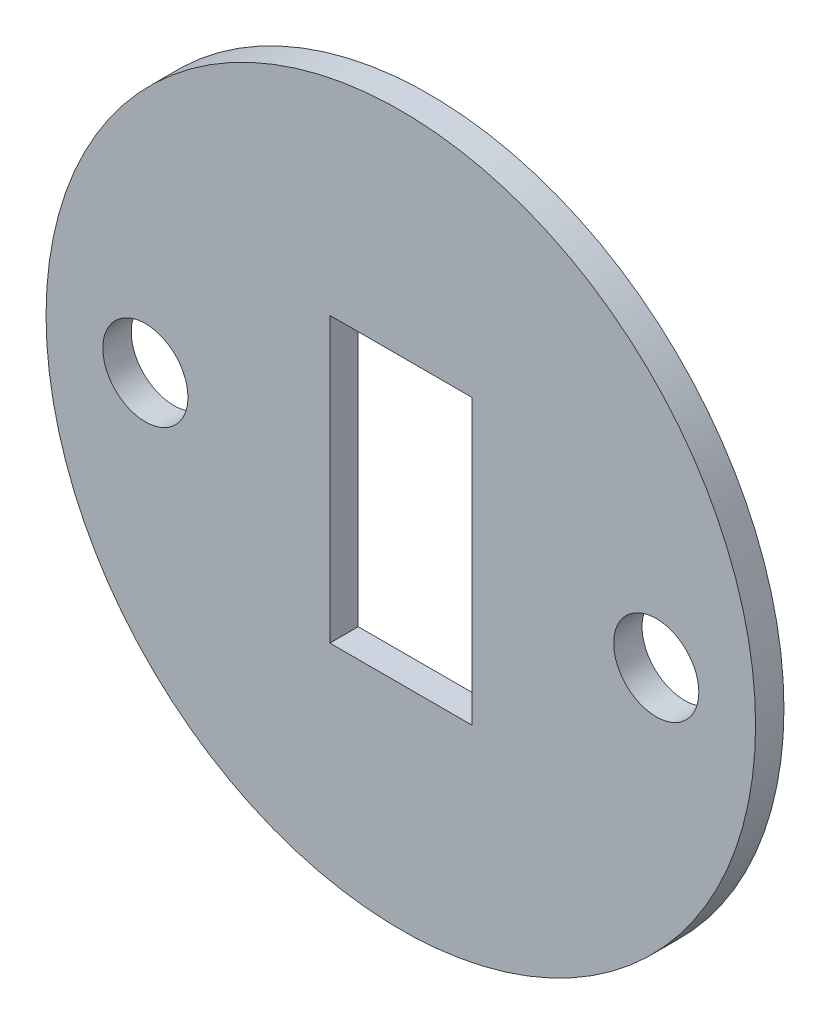
SolidWorks part; units mm, degrees
ref_plane "前视基准面" through (0, 0, 0) normal (0, 0, 1) x (1, 0, 0)
ref_plane "上视基准面" through (0, 0, 0) normal (0, 1, 0) x (1, 0, 0)
ref_plane "右视基准面" through (0, 0, 0) normal (1, 0, 0) x (0, 0, -1)
other "Configuration Table"
sketch "Sketch1" plane through (0, 0, 0) normal (0, 0, 1) x (1, 0, 0)
  circle A0 centre (0, 0) radius 25
extrude "Boss-Extrude1" add sketch "Sketch1" along normal blind 2
sketch "Sketch2" plane through (0, 0, 0) normal (0, 0, 1) x (1, 0, 0)
  line L1 (-5, -10) -> (5, -10)
  line L2 (-5, -10) -> (-5, 10)
  line L3 (-5, 10) -> (5, 10)
  line L4 (5, -10) -> (5, 10)
  line L5 (-5, -10) -> (5, 10) construction
  line L6 (-5, 10) -> (5, -10) construction
  point P0 (0, 0)
extrude "Cut-Extrude1" cut sketch "Sketch2" along normal blind 5
sketch "Sketch3" plane through (0, 0, 0) normal (0, 0, 1) x (1, 0, 0)
  circle A0 centre (-18, 0) radius 3
  circle A1 centre (18, 0) radius 3
extrude "Cut-Extrude2" cut sketch "Sketch3" along normal blind 5
